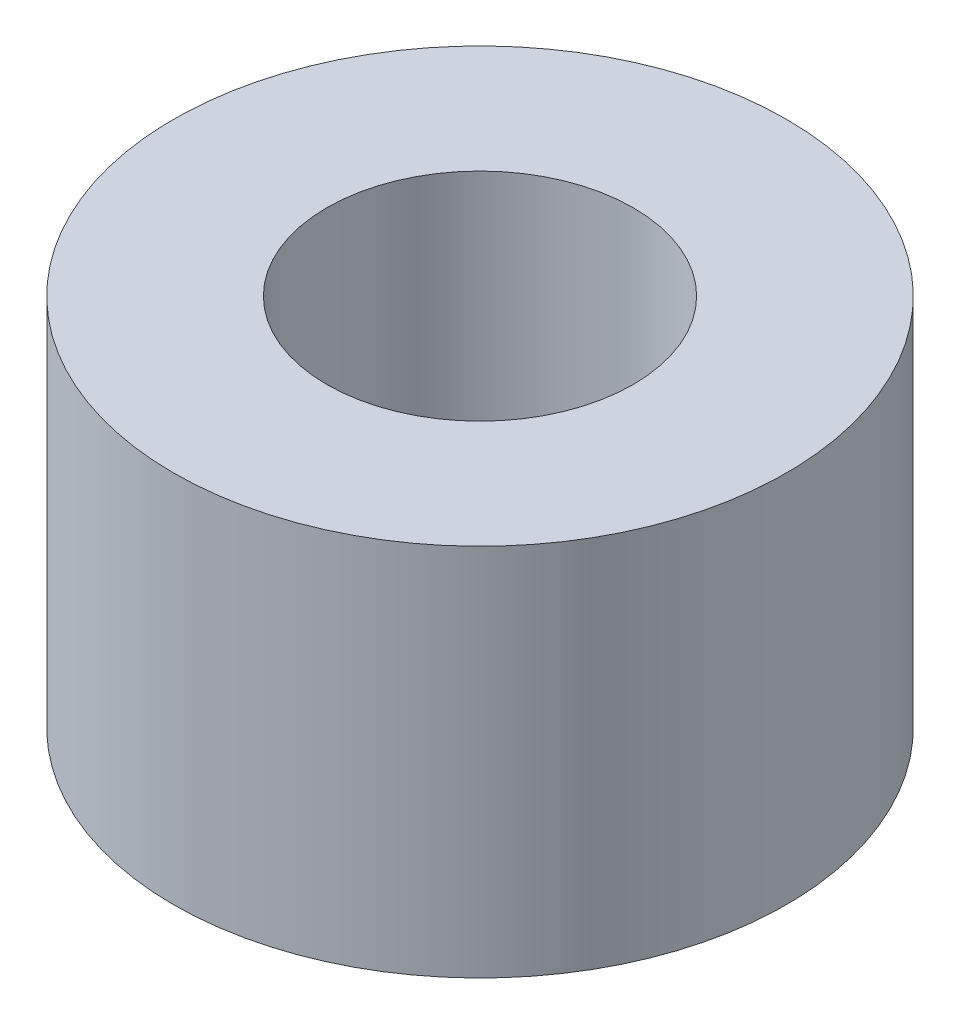
SolidWorks part; units mm, degrees
ref_plane "Front Plane" through (0, 0, 0) normal (0, 0, 1) x (1, 0, 0)
ref_plane "Top Plane" through (0, 0, 0) normal (0, 1, 0) x (1, 0, 0)
ref_plane "Right Plane" through (0, 0, 0) normal (1, 0, 0) x (0, 0, -1)
sketch "Sketch1" plane through (0, 0, 0) normal (0, 1, 0) x (1, 0, 0)
  circle A0 centre (0, 0) radius 25.4
  circle A1 centre (0, 0) radius 12.7
  dimension "D1" = 25.4
  dimension "D2" = 50.8
extrude "Boss-Extrude1" add sketch "Sketch1" along normal blind 31
